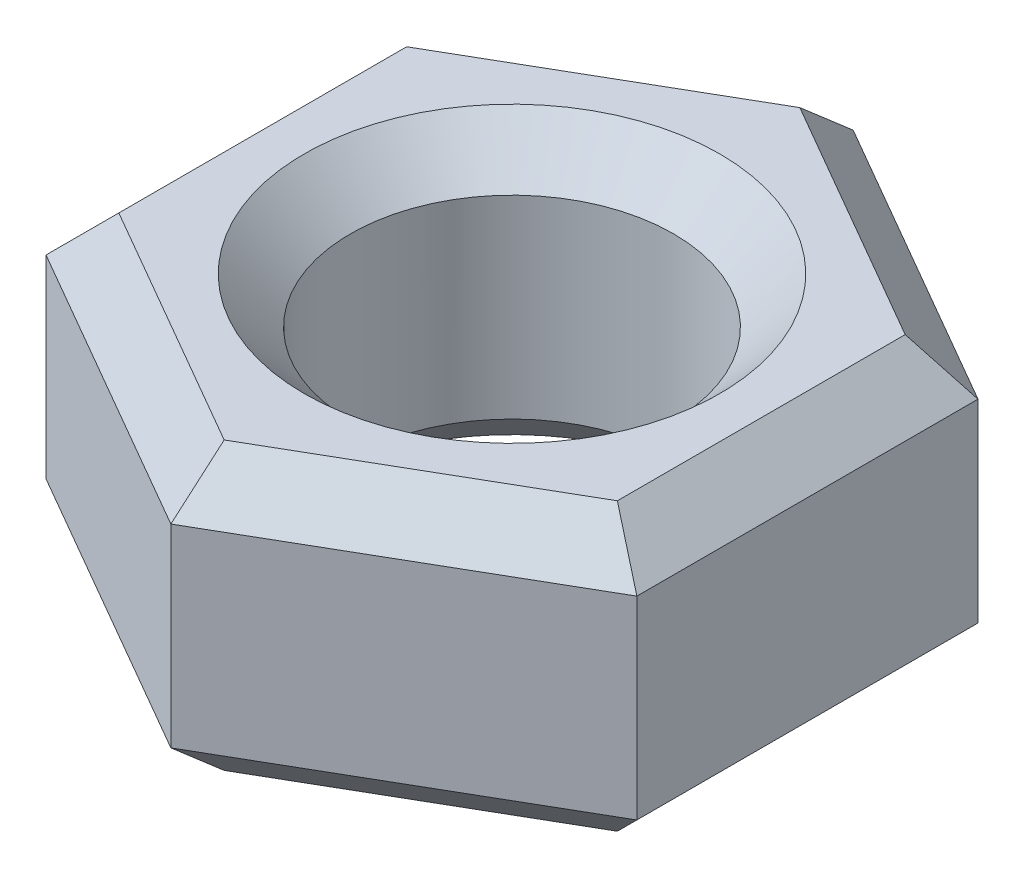
SolidWorks part; units mm, degrees
ref_plane "Front Plane" through (0, 0, 0) normal (0, 0, 1) x (1, 0, 0)
ref_plane "Top Plane" through (0, 0, 0) normal (0, 1, 0) x (1, 0, 0)
ref_plane "Right Plane" through (0, 0, 0) normal (1, 0, 0) x (0, 0, -1)
sketch "Sketch1" plane through (0, 0, 0) normal (0, 1, 0) x (1, 0, 0)
  line L0 (0, 0) -> (0, 6.1868) construction
  line L1 (6.4, -3.695) -> (6.4, 3.695)
  line L2 (6.4, 3.695) -> (0, 7.3901)
  line L3 (0, 7.3901) -> (-6.4, 3.695)
  line L4 (-6.4, 3.695) -> (-6.4, -3.695)
  line L5 (-6.4, -3.695) -> (0, -7.3901)
  line L6 (0, -7.3901) -> (6.4, -3.695)
  line L7 (0, 0) -> (6.4, 0) construction
  circle A0 centre (0, 0) radius 6.4 construction
  circle A1 centre (0, 0) radius 3.5
  dimension "D1" = 12.8
  dimension "D2" = 7
  dimension "D3" = 90
extrude "Boss-Extrude1" add sketch "Sketch1" along normal blind 6.2
chamfer "Chamfer1" distance 1 angle 45 14 edges at (0, 0, 3.5) (6.4, 0, 0) (3.2, 0, -5.5426) (-3.2, 0, -5.5426) (-6.4, 0, 0) (-3.2, 0, 5.5426) (3.2, 0, 5.5426) (0, 6.2, 3.5) (-3.2, 6.2, 5.5426) (-6.4, 6.2, 0) (-3.2, 6.2, -5.5426) (3.2, 6.2, -5.5426) (6.4, 6.2, 0) (3.2, 6.2, 5.5426)
